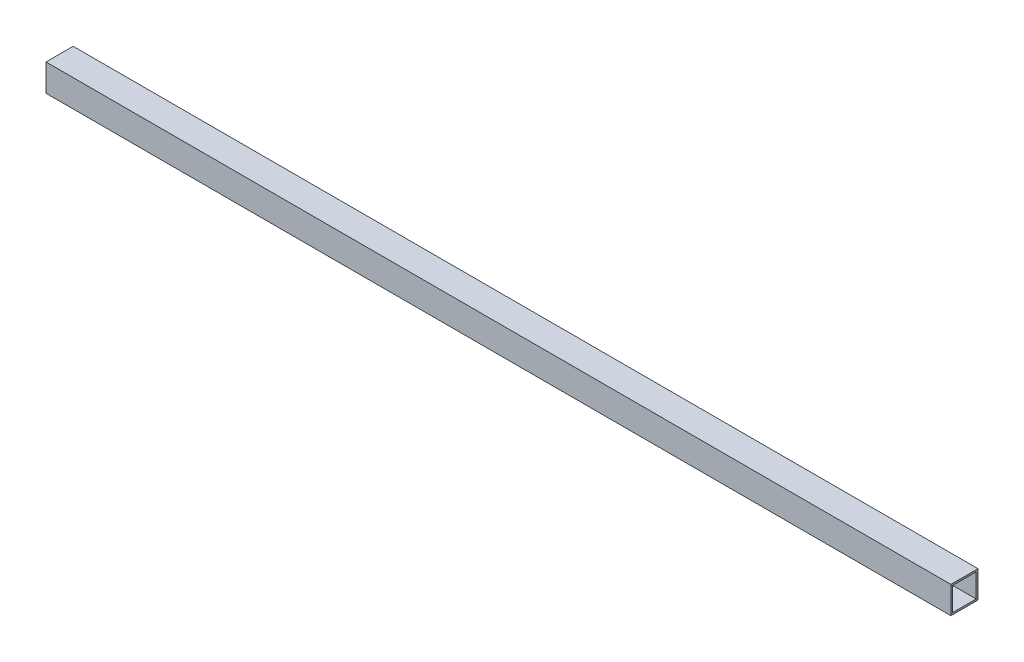
SolidWorks part; units mm, degrees
ref_plane "Piano frontale" through (0, 0, 0) normal (0, 0, 1) x (1, 0, 0)
ref_plane "Piano superiore" through (0, 0, 0) normal (0, 1, 0) x (1, 0, 0)
ref_plane "Piano destro" through (0, 0, 0) normal (1, 0, 0) x (0, 0, -1)
sketch "Schizzo1" plane through (0, 0, 0) normal (1, 0, 0) x (0, 0, -1)
  line L1 (-7.5, -7.5) -> (7.5, -7.5)
  line L2 (-7.5, -7.5) -> (-7.5, 7.5)
  line L3 (-7.5, 7.5) -> (7.5, 7.5)
  line L4 (7.5, -7.5) -> (7.5, 7.5)
  line L5 (-7.5, -7.5) -> (7.5, 7.5) construction
  line L6 (-7.5, 7.5) -> (7.5, -7.5) construction
  line L7 (-6.5, -6.5) -> (6.5, -6.5)
  line L8 (-6.5, -6.5) -> (-6.5, 6.5)
  line L9 (-6.5, 6.5) -> (6.5, 6.5)
  line L10 (6.5, -6.5) -> (6.5, 6.5)
  line L11 (-6.5, -6.5) -> (6.5, 6.5) construction
  line L12 (-6.5, 6.5) -> (6.5, -6.5) construction
  point P0 (0, 0)
  point P6 (0, 0)
  dimension "D1" = 15
  dimension "D2" = 15
  dimension "D3" = 13
extrude "Estrusione-Estrusione1" add sketch "Schizzo1" along normal blind 500
